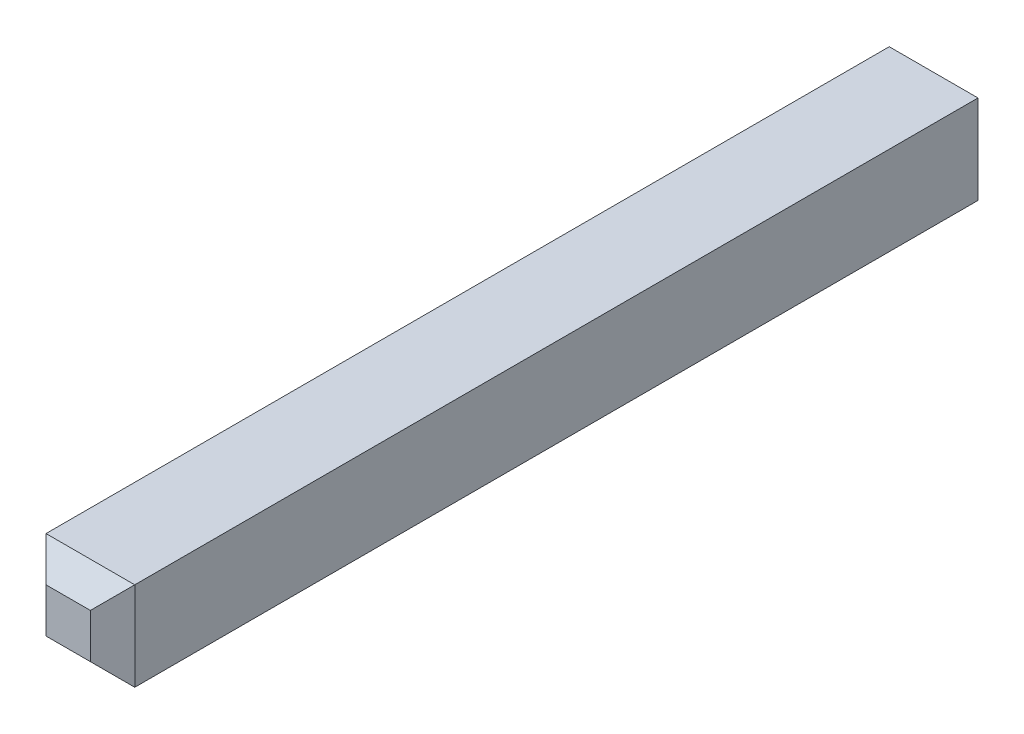
SolidWorks part; units mm, degrees
ref_plane "Plan de face" through (0, 0, 0) normal (0, 0, 1) x (1, 0, 0)
ref_plane "Plan de dessus" through (0, 0, 0) normal (0, 1, 0) x (1, 0, 0)
ref_plane "Plan de droite" through (0, 0, 0) normal (1, 0, 0) x (0, 0, -1)
sketch "Esquisse1" plane through (0, 0, 0) normal (0, 0, 1) x (1, 0, 0)
  line L1 (0, 0) -> (4, 0)
  line L2 (0, 0) -> (0, 4)
  line L3 (0, 4) -> (4, 4)
  line L4 (4, 0) -> (4, 4)
  dimension "D1" = 4
extrude "Boss.-Extru.1" add sketch "Esquisse1" along normal blind 40
chamfer "Chanfrein1" distance 1 angle 45 8 edges at (2, 0, 0) (4, 2, 0) (2, 4, 0) (0, 2, 0) (2, 4, 40) (4, 2, 40) (2, 0, 40) (0, 2, 40)
